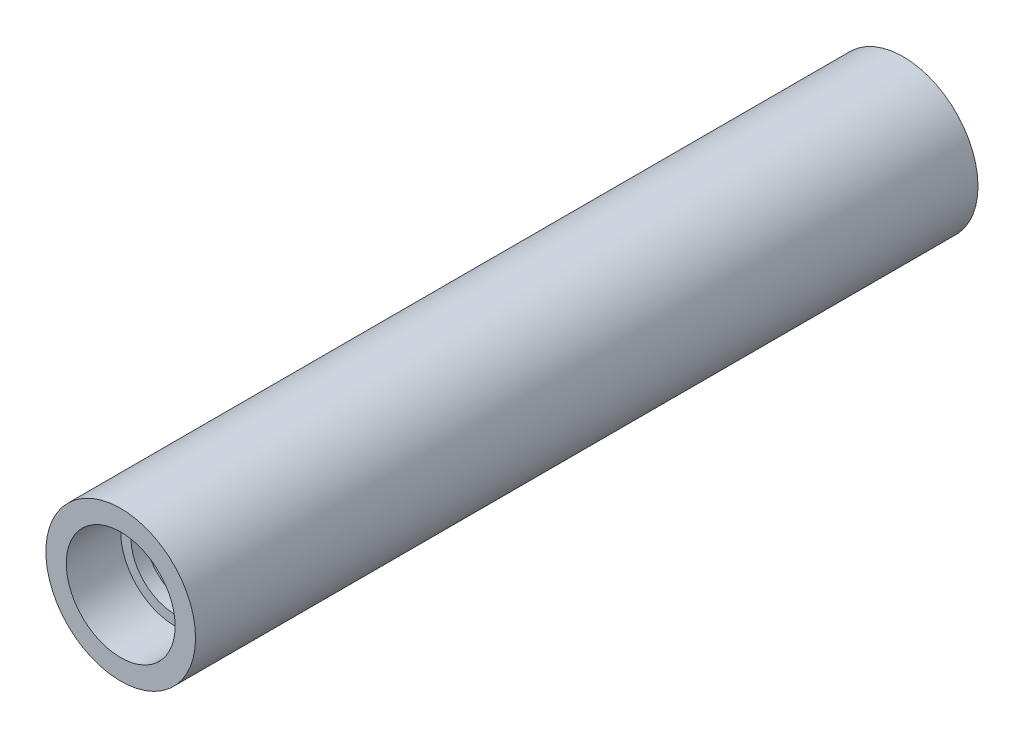
SolidWorks part; units mm, degrees
material "6061 Alloy"
ref_plane "Front Plane" through (0, 0, 0) normal (0, 0, 1) x (1, 0, 0)
ref_plane "Top Plane" through (0, 0, 0) normal (0, 1, 0) x (1, 0, 0)
ref_plane "Right Plane" through (0, 0, 0) normal (1, 0, 0) x (0, 0, -1)
sketch "Sketch1" plane through (0, 0, 0) normal (0, 0, 1) x (1, 0, 0)
  circle A0 centre (0, 0) radius 11
  circle A1 centre (0, 0) radius 8
  dimension "Bore" = 16
  dimension "D1" = 22
extrude "Boss-Extrude1" add sketch "Sketch1" along normal mid plane 115
sketch "Sketch2" plane through (0, 0, 0) normal (0, 0, 1) x (1, 0, 0)
  circle A0 centre (0, 0) radius 6.5
  circle A1 centre (0, 0) radius 8
  dimension "D1" = 16
  dimension "D2" = 13
extrude "Boss-Extrude2" add sketch "Sketch2" along normal blind 2 from offset 47.5
mirror "Mirror1" about plane through (0, 0, 0) normal (0, 0, 1) of "Boss-Extrude2"
sketch "Sketch3" plane through (0, 0, 0) normal (0, 1, 0) x (1, 0, 0)
  line L0 (0, 37.5) -> (0, -37.5) construction
  line L1 (0, 35) -> (0, -35) construction
  line L2 (-8, 0) -> (8, 0) construction
  line L3 (11, 0) -> (-11, 0) construction
  point P4 (0, 0)
  point P8 (0, 0)
  point P11 (0, 0)
  point P13 (0, 0)
  dimension "Stroke" = 75
  dimension "C" = 70
  dimension "G" = 16
  dimension "U" = 22
equation "\"D2@Sketch2\"=\"D1@Sketch2\"-3"
equation "\"D19@Boss-Extrude2\"=\"Stroke\"/2 +10"
equation "\"D1@Boss-Extrude1\"=\"C@Sketch3\"+\"Stroke\"-2*\"G@Sketch3\"+2"
equation "\"D1@Sketch1\"=\"U@Sketch3\""
equation "\"D1@Sketch2\"= \"Bore@Sketch1\""
equation "\"Stroke\" = 75mm'Standard Strole [25 50 75 80 100 125 150 160 175 200 250 300 350 400 450 500]"
equation "\"Stroke@Sketch3\"=\"Stroke\""
